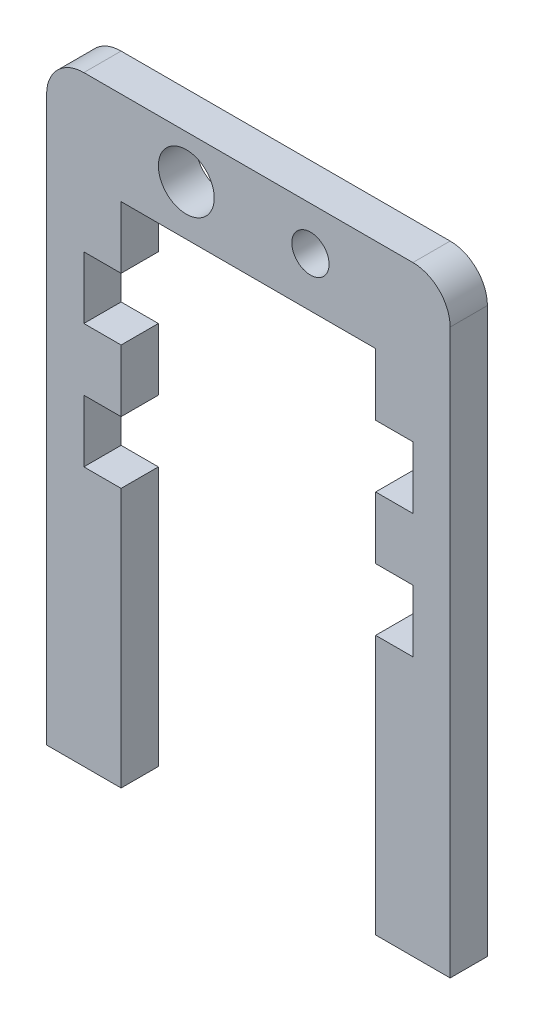
SolidWorks part; units mm, degrees
ref_plane "Alzado" through (0, 0, 0) normal (0, 0, 1) x (1, 0, 0)
ref_plane "Planta" through (0, 0, 0) normal (0, 1, 0) x (1, 0, 0)
ref_plane "Vista lateral" through (0, 0, 0) normal (1, 0, 0) x (0, 0, -1)
sketch "Sketch1" plane through (0, 0, 0) normal (0, 0, 1) x (1, 0, 0)
  line L0 (-13.25, 27.95) -> (13.25, 27.95)
  line L1 (-10.25, 20.45) -> (10.25, 20.45)
  line L2 (-10.25, 20.45) -> (-10.25, 15.45)
  line L3 (-10.25, -20.45) -> (10.25, -20.45)
  line L4 (10.25, 20.45) -> (10.25, 15.45)
  line L5 (-10.25, 20.45) -> (10.25, -20.45) construction
  line L6 (-10.25, -20.45) -> (10.25, 20.45) construction
  line L7 (16.25, 24.95) -> (16.25, -24.95)
  line L8 (13.25, -27.95) -> (-13.25, -27.95)
  line L9 (-16.25, -24.95) -> (-16.25, 24.95)
  line L10 (0, 27.95) -> (0, -27.95) construction
  line L11 (16.25, 0) -> (-16.25, 0) construction
  line L12 (-10.25, 15.45) -> (-13.25, 15.45)
  line L13 (-13.25, 15.45) -> (-13.25, 10.45)
  line L14 (-13.25, 10.45) -> (-10.25, 10.45)
  line L15 (-10.25, 5.45) -> (-13.25, 5.45)
  line L16 (-13.25, 5.45) -> (-13.25, 0.45)
  line L17 (-13.25, 0.45) -> (-10.25, 0.45)
  line L18 (10.25, 15.45) -> (13.25, 15.45)
  line L19 (13.25, 15.45) -> (13.25, 10.45)
  line L20 (13.25, 10.45) -> (10.25, 10.45)
  line L21 (10.25, 5.45) -> (13.25, 5.45)
  line L22 (13.25, 5.45) -> (13.25, 0.45)
  line L23 (13.25, 0.45) -> (10.25, 0.45)
  line L24 (-10.25, 10.45) -> (-10.25, 5.45)
  line L25 (-10.25, 0.45) -> (-10.25, -20.45)
  line L26 (10.25, 0.45) -> (10.25, -20.45)
  line L27 (10.25, 10.45) -> (10.25, 5.45)
  line L28 (-5, 24.45) -> (5, 24.45) construction
  arc A0 (13.25, 27.95) -> (16.25, 24.95) centre (13.25, 24.95) cw
  arc A1 (16.25, -24.95) -> (13.25, -27.95) centre (13.25, -24.95) cw
  arc A2 (-13.25, -27.95) -> (-16.25, -24.95) centre (-13.25, -24.95) cw
  arc A3 (-16.25, 24.95) -> (-13.25, 27.95) centre (-13.25, 24.95) cw
  circle A4 centre (-5, 24.45) radius 2.25
  circle A5 centre (5, 24.45) radius 1.5
  circle A6 centre (5, -24.45) radius 1.5
  circle A7 centre (-5, -24.45) radius 2.25
  point P0 (0, 0)
  point P22 (0, 0)
  dimension "D4" = 3
  dimension "D14" = 4.5
  dimension "D15" = 3
  dimension "D1" = 20.5
  dimension "D2" = 40.9
  dimension "D3" = 7.5
  dimension "D5" = 6
  dimension "D6" = 3
  dimension "D7" = 3
  dimension "D8" = 5
  dimension "D9" = 5
  dimension "D10" = 5
  dimension "D11" = 5
  dimension "D12" = 4
  dimension "D13" = 10
extrude "Boss-Extrude1" add sketch "Sketch1" along normal blind 3
sketch "Croquis1" plane through (0, 0, 3) normal (0, 0, 1) x (1, 0, 0)
  line L1 (-16.25, -27.95) -> (16.25, -27.95)
  line L2 (-16.25, -27.95) -> (-16.25, -20.45)
  line L3 (-16.25, -20.45) -> (16.25, -20.45)
  line L4 (16.25, -27.95) -> (16.25, -20.45)
  line L5 (-16.25, -27.95) -> (16.25, -20.45) construction
  line L6 (-16.25, -20.45) -> (16.25, -27.95) construction
  line L8 (-10.25, -20.45) -> (10.25, -20.45) construction
  line L9 (-13.25, -27.95) -> (13.25, -27.95) construction
  line L10 (16.25, -24.95) -> (16.25, 24.95) construction
  line L11 (-16.25, 24.95) -> (-16.25, -24.95) construction
  point P0 (0, -24.2)
extrude "Cortar-Extruir1" cut sketch "Croquis1" against normal up to next
